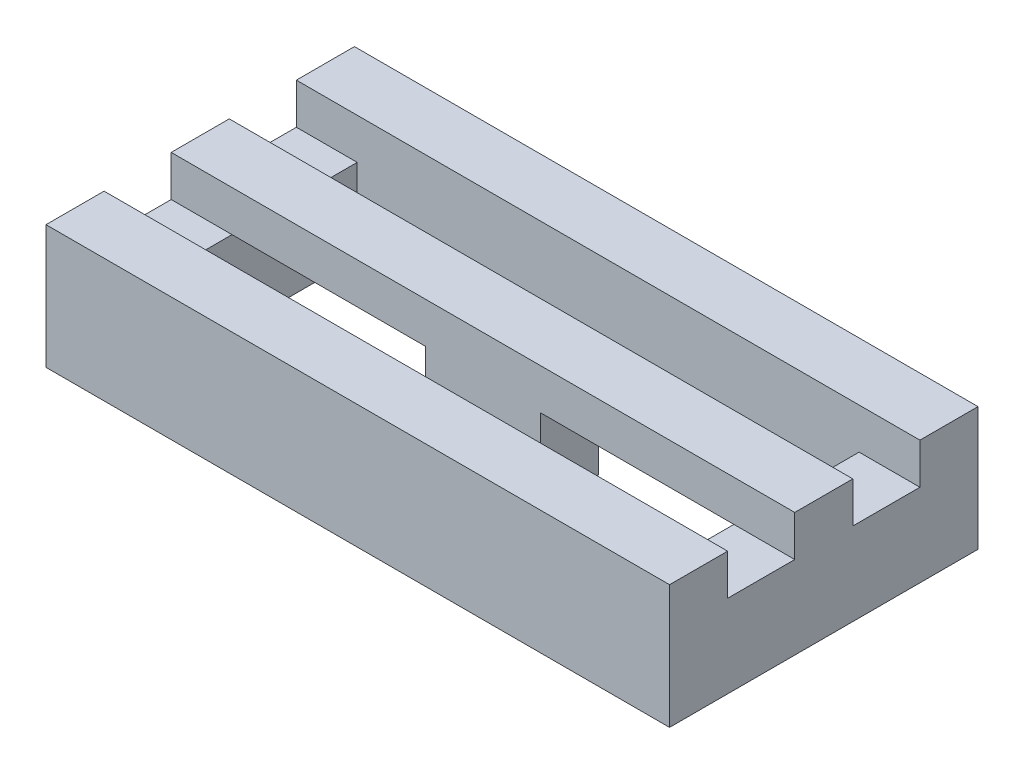
SolidWorks part; units mm, degrees
ref_plane "Front Plane" through (0, 0, 0) normal (0, 0, 1) x (1, 0, 0)
ref_plane "Top Plane" through (0, 0, 0) normal (0, 1, 0) x (1, 0, 0)
ref_plane "Right Plane" through (0, 0, 0) normal (1, 0, 0) x (0, 0, -1)
sketch "Sketch1" plane through (0, 0, 0) normal (0, 1, 0) x (1, 0, 0)
  line L1 (-7.945, 3.93) -> (7.945, 3.93)
  line L2 (-7.945, 3.93) -> (-7.945, -3.93)
  line L3 (-7.945, -3.93) -> (7.945, -3.93)
  line L4 (7.945, 3.93) -> (7.945, -3.93)
  line L5 (-7.945, 3.93) -> (7.945, -3.93) construction
  line L6 (-7.945, -3.93) -> (7.945, 3.93) construction
  point P0 (0, 0)
  dimension "D1" = 7.86
  dimension "D2" = 15.89
extrude "Boss-Extrude1" add sketch "Sketch1" against normal blind 3.15
sketch "Sketch2" plane through (7.945, 0, 0) normal (1, 0, 0) x (0, 0, -1)
  line L0 (0.74, 0) -> (0.74, -1.04)
  line L1 (-3.93, 0) -> (3.93, 0) construction
  line L2 (0.74, -1.04) -> (2.45, -1.04)
  line L3 (2.45, -1.04) -> (2.45, 0)
  line L4 (2.45, 0) -> (0.74, 0)
  line L5 (-2.45, 0) -> (-2.45, -1.04)
  line L6 (-2.45, -1.04) -> (-0.74, -1.04)
  line L7 (-0.74, -1.04) -> (-0.74, 0)
  line L8 (-0.74, 0) -> (-2.45, 0)
  line L9 (3.93, -3.15) -> (3.93, 0) construction
  line L10 (-3.93, -3.15) -> (-3.93, 0) construction
  dimension "D1" = 1.48
  dimension "D2" = 1.48
  dimension "D3" = 1.48
  dimension "D4" = 1.71
  dimension "D5" = 1.04
  dimension "D6" = 1.04
extrude "Cut-Extrude1" cut sketch "Sketch2" against normal through all
sketch "Sketch3" plane through (0, -1.04, 0) normal (0, 1, 0) x (1, 0, 0)
  line L0 (-6.395, 2.45) -> (-6.395, 0.74)
  line L1 (-7.945, 2.45) -> (7.945, 2.45) construction
  line L2 (-7.945, 0.74) -> (7.945, 0.74) construction
  line L3 (-6.395, 0.74) -> (6.395, 0.74)
  line L4 (-7.945, 0.74) -> (7.945, 0.74) construction
  line L5 (6.395, 0.74) -> (6.395, 2.45)
  line L6 (-7.945, 2.45) -> (7.945, 2.45) construction
  line L7 (6.395, 2.45) -> (-6.395, 2.45)
  line L8 (7.945, 0.74) -> (7.945, 2.45) construction
  line L9 (-7.945, 0.74) -> (-7.945, 2.45) construction
  line L10 (-6.395, -0.74) -> (-6.395, -2.45)
  line L11 (-7.945, -0.74) -> (7.945, -0.74) construction
  line L12 (-7.945, -2.45) -> (7.945, -2.45) construction
  line L13 (-6.395, -2.45) -> (6.395, -2.45)
  line L14 (6.395, -2.45) -> (6.395, -0.74)
  line L15 (-7.945, -0.74) -> (7.945, -0.74) construction
  line L16 (6.395, -0.74) -> (-6.395, -0.74)
  dimension "D1" = 1.55
  dimension "D2" = 1.55
extrude "Cut-Extrude2" cut sketch "Sketch3" against normal through all
sketch "Sketch4" plane through (0, 0, 0.74) normal (0, 0, 1) x (1, 0, 0)
  line L1 (-6.395, -1.04) -> (-1.465, -1.04)
  line L2 (-1.465, -1.04) -> (-1.465, -3.15)
  line L3 (6.395, -3.15) -> (-6.395, -3.15) construction
  line L4 (-1.465, -3.15) -> (-6.395, -3.15)
  line L5 (-6.395, -3.15) -> (-6.395, -1.04) construction
  line L6 (-6.395, -3.15) -> (-6.395, -1.04)
  line L7 (6.395, -1.04) -> (6.395, -3.15)
  line L8 (6.395, -3.15) -> (6.395, -1.04) construction
  line L9 (6.395, -3.15) -> (1.465, -3.15)
  line L10 (1.465, -3.15) -> (1.465, -1.04)
  line L11 (1.465, -1.04) -> (6.395, -1.04)
  dimension "D1" = 2.93
  dimension "D2" = 4.93
extrude "Cut-Extrude3" cut sketch "Sketch4" against normal blind 1.6
